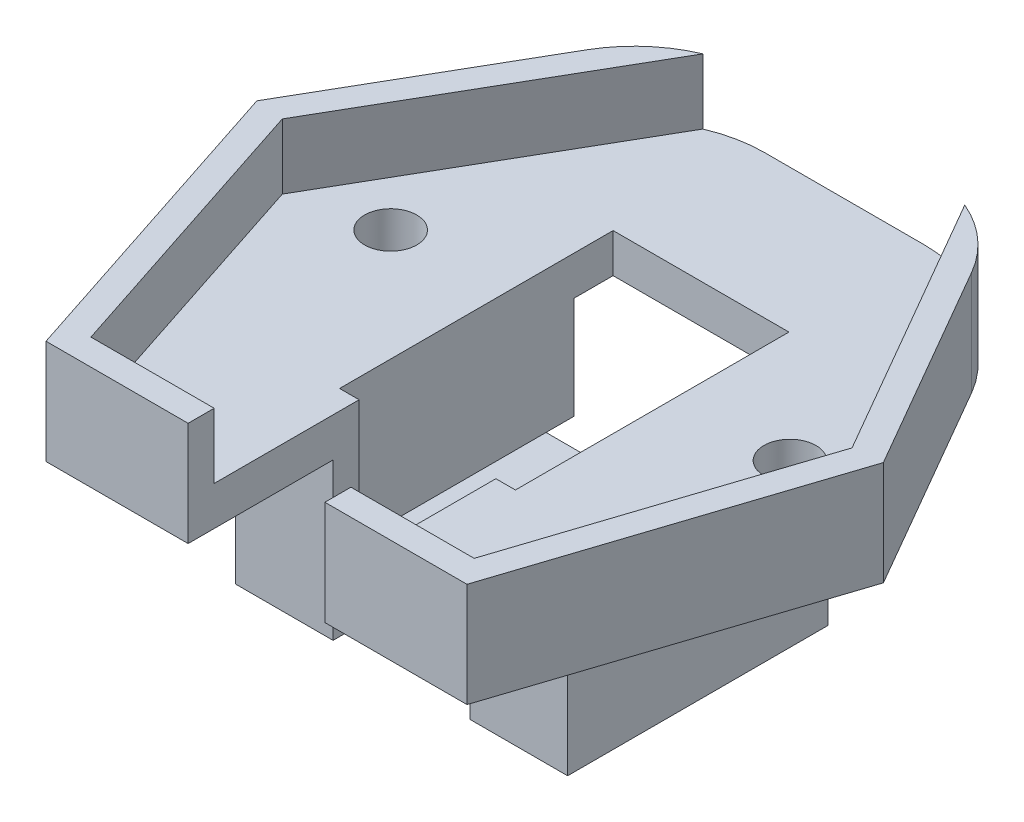
SolidWorks part; units mm, degrees
ref_plane "Front Plane" through (0, 0, 0) normal (0, 0, 1) x (1, 0, 0)
ref_plane "Top Plane" through (0, 0, 0) normal (0, 1, 0) x (1, 0, 0)
ref_plane "Right Plane" through (0, 0, 0) normal (1, 0, 0) x (0, 0, -1)
sketch "Sketch1" plane through (0, 0, 0) normal (0, 1, 0) x (1, 0, 0)
  line L2 (9.0115, 6.4961) -> (-9.0115, 6.4961) construction
  line L6 (-9.0115, 6.4961) -> (-21.3279, -14.8365) construction
  line L7 (-21.3279, -14.8365) -> (-14.35, -36.1328) construction
  line L10 (-21.3279, -14.8365) -> (-16.4146, -17.6732) construction
  line L12 (9.3001, 6.9961) -> (-9.3001, 6.9961)
  line L13 (-9.3001, 6.9961) -> (-21.8726, -14.7799)
  line L14 (-21.8726, -14.7799) -> (-14.7123, -36.6328)
  line L15 (-21.3279, -14.8365) -> (-11.8982, 1.4961) construction
  line L20 (-10.4548, 8.9961) -> (-24.0513, -14.5537)
  line L21 (-24.0513, -14.5537) -> (-16.1616, -38.6328)
  line L25 (21.3279, -36.1328) -> (-21.3279, -36.1328) construction
  line L26 (9.0115, 6.4961) -> (21.3279, -14.8365) construction
  line L27 (21.3279, -14.8365) -> (9.0115, 6.4961) construction
  line L28 (-14.35, -36.1328) -> (21.3279, -36.1328) construction
  line L29 (21.3279, -36.1328) -> (21.3279, -14.8365) construction
  line L30 (0, 8.9961) -> (0, -38.6328) construction
  line L31 (9.3001, 6.9961) -> (21.8726, -14.7799)
  line L32 (10.4548, 8.9961) -> (24.0513, -14.5537)
  line L33 (-16.1616, -38.6328) -> (23.8279, -38.6328) construction
  line L34 (-14.7123, -36.6328) -> (21.8279, -36.6328) construction
  line L35 (21.8279, -36.6328) -> (21.8279, -14.7025) construction
  line L36 (23.8279, -38.6328) -> (23.8279, -14.1666) construction
  line L37 (10.4548, 8.9961) -> (-10.4548, 8.9961) construction
  line L38 (21.8279, -14.7025) -> (9.3001, 6.9961) construction
  line L39 (23.8279, -14.1666) -> (10.4548, 8.9961) construction
  line L40 (24.0513, -14.5537) -> (16.1616, -38.6328)
  line L41 (21.8726, -14.7799) -> (14.7123, -36.6328)
  line L42 (21.3279, -14.8365) -> (14.35, -36.1328) construction
  line L43 (-14.7123, -36.6328) -> (14.7123, -36.6328)
  line L44 (-16.1616, -38.6328) -> (16.1616, -38.6328)
  line L45 (-10.4548, 8.9961) -> (10.4548, 8.9961)
  dimension "D1" = 0.5
  dimension "D2" = 2
extrude "Boss-Extrude1" add sketch "Sketch1" along normal blind 5
sketch "Sketch2" plane through (0, 0, 0) normal (0, -1, 0) x (-1, 0, 0)
  line L8 (24.0513, -14.5537) -> (10.4548, 8.9961)
  line L9 (10.4548, 8.9961) -> (-10.4548, 8.9961)
  line L12 (-10.4548, 8.9961) -> (-24.0513, -14.5537)
  line L13 (-24.0513, -14.5537) -> (-16.1616, -38.6328)
  line L14 (-16.1616, -38.6328) -> (16.1616, -38.6328)
  line L15 (16.1616, -38.6328) -> (24.0513, -14.5537)
extrude "Boss-Extrude2" add sketch "Sketch2" along normal blind 3
sketch "Sketch3" plane through (0, -3, 0) normal (0, -1, 0) x (-1, 0, 0)
  line L0 (0, 8.4961) -> (0, -38.1421) construction
  line L1 (10.0247, 8.4961) -> (-10.0247, 8.4961) construction
  line L2 (-17.6488, -38.1421) -> (17.6488, -38.1421) construction
  line L3 (5.25, -7.5039) -> (12.7574, -7.5039)
  line L4 (5.25, -7.5039) -> (-5.25, -7.5039) construction
  line L5 (5.25, -7.5039) -> (5.25, -27.5039)
  line L6 (5.25, -27.5039) -> (-5.25, -27.5039) construction
  line L7 (-5.25, -7.5039) -> (-5.25, -27.5039)
  line L8 (10.4548, 8.9961) -> (-10.4548, 8.9961) construction
  line L10 (12.7574, -7.5039) -> (12.7574, -27.5039)
  line L11 (12.7574, -27.5039) -> (5.25, -27.5039)
  line L12 (-12.7574, -27.5039) -> (-5.25, -27.5039)
  line L13 (-12.7574, -7.5039) -> (-12.7574, -27.5039)
  line L14 (-5.25, -7.5039) -> (-12.7574, -7.5039)
  dimension "D1" = 10.5
  dimension "D2" = 20
  dimension "D3" = 16.5
extrude "Boss-Extrude3" add sketch "Sketch3" along normal blind 12
sketch "Sketch5" plane through (0, 0, 7.5039) normal (0, 0, -1) x (-1, 0, 0)
  line L0 (0, -3) -> (0, -15.9929) construction
  line L1 (10.0247, -3) -> (-10.0247, -3) construction
  line L2 (-5.25, -15) -> (-5.25, -3) construction
  line L3 (-9.75, -13) -> (9.75, -13)
  line L4 (-9.75, -13) -> (-9.75, -10.85)
  line L5 (-9.75, -10.85) -> (-6.75, -10.85)
  line L6 (9.75, -13) -> (9.75, -10.85)
  line L7 (-9.75, -13) -> (9.75, -10.85) construction
  line L8 (-9.75, -10.85) -> (9.75, -13) construction
  line L9 (-5.25, -15) -> (-12.7574, -15) construction
  line L10 (-5.25, -3) -> (-12.7574, -3) construction
  line L12 (-5.25, -10.85) -> (-5.25, -3)
  line L13 (-5.25, -3) -> (-6.75, -3)
  line L14 (-6.75, -10.85) -> (-6.75, -3)
  line L15 (5.25, -3) -> (6.75, -3)
  line L16 (6.75, -10.85) -> (6.75, -3)
  line L18 (5.25, -10.85) -> (5.25, -3)
  line L19 (-5.25, -10.85) -> (5.25, -10.85)
  line L20 (6.75, -10.85) -> (9.75, -10.85)
  point P5 (0, -11.925)
  dimension "D1" = 4.5
  dimension "D2" = 2
  dimension "D3" = 2.15
  dimension "D4" = 1.5
extrude "Cut-Extrude2" cut sketch "Sketch5" against normal blind 18
sketch "Sketch6" plane through (0, -3, 0) normal (0, -1, 0) x (-1, 0, 0)
  line L0 (0, 8.9913) -> (0, -38.6328) construction
  line L9 (-5.25, -25.5039) -> (-6.75, -25.5039) construction
  line L26 (-5.25, -38.6328) -> (5.25, -38.6328)
  line L28 (6.75, -7.5039) -> (6.75, -25.5039)
  line L29 (6.75, -25.5039) -> (5.25, -25.5039)
  line L30 (-6.75, -7.5039) -> (-6.75, -25.5039)
  line L31 (-6.75, -25.5039) -> (-6.75, -7.5039) construction
  line L32 (-5.25, -25.5039) -> (-6.75, -25.5039)
  line L39 (6.75, -4.5039) -> (-6.75, -4.5039)
  line L44 (-6.75, -4.5039) -> (-6.75, -25.5039)
  line L45 (6.75, -4.5039) -> (6.75, -25.5039)
  line L46 (-5.25, -25.5039) -> (-5.25, -38.6328)
  line L47 (5.25, -25.5039) -> (5.25, -38.6328)
  line L48 (-23.8279, -14.1666) -> (-23.8279, -38.6328) construction
  line L49 (10.4548, 8.9961) -> (-10.4548, 8.9961) construction
  circle A0 centre (-15.3279, -13.0039) radius 2
  circle A1 centre (15.3279, -13.0039) radius 2
  point P31 (0, 0.677)
  dimension "D1" = 4
  dimension "D2" = 8.5
  dimension "D3" = 22
extrude "Cut-Extrude3" cut sketch "Sketch6" against normal through all
sketch "Sketch7" plane through (0, -3, 0) normal (0, -1, 0) x (-1, 0, 0)
  line L0 (10.0247, 8.4961) -> (-10.0247, 8.4961) construction
  line L1 (12.0247, 10.4961) -> (-12.0247, 10.4961)
  line L2 (12.0247, 10.4961) -> (12.0247, 6.4961)
  line L3 (12.0247, 6.4961) -> (-12.0247, 6.4961)
  line L4 (-12.0247, 10.4961) -> (-12.0247, 6.4961)
  line L5 (12.0247, 10.4961) -> (-12.0247, 6.4961) construction
  line L6 (12.0247, 6.4961) -> (-12.0247, 10.4961) construction
  line L7 (-10.0247, 8.4961) -> (-29.3492, -10.8283) construction
  point P0 (0, 8.4961)
  dimension "D1" = 4
extrude "Cut-Extrude4" cut sketch "Sketch7" against normal blind 10
fillet "Fillet1" radius 10 2 edges at (-11.8982, 1, -6.4961) (11.8982, 1, -6.4961)
